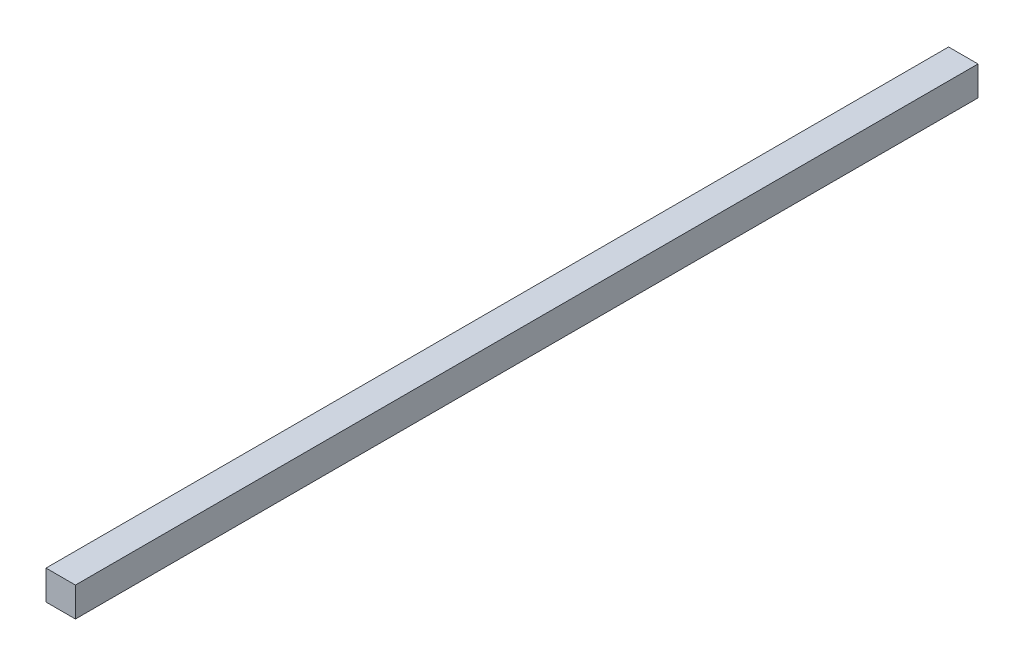
SolidWorks part; units mm, degrees
ref_plane "Front Plane" through (0, 0, 0) normal (0, 0, 1) x (1, 0, 0)
ref_plane "Top Plane" through (0, 0, 0) normal (0, 1, 0) x (1, 0, 0)
ref_plane "Right Plane" through (0, 0, 0) normal (1, 0, 0) x (0, 0, -1)
sketch "Sketch2" plane through (0, 0, 0) normal (0, 0, 1) x (1, 0, 0)
  line L0 (-25.4, 762) -> (25.4, 762) construction
  line L1 (-18.789, 711.2) -> (19.311, 711.2)
  line L2 (-18.789, 711.2) -> (-18.789, 673.1)
  line L3 (-18.789, 673.1) -> (19.311, 673.1)
  line L4 (19.311, 711.2) -> (19.311, 673.1)
  dimension "D1" = 38.1
  dimension "D2" = 38.1
  dimension "D3" = 50.8
extrude "Boss-Extrude1" add sketch "Sketch2" along normal blind 1168.4
